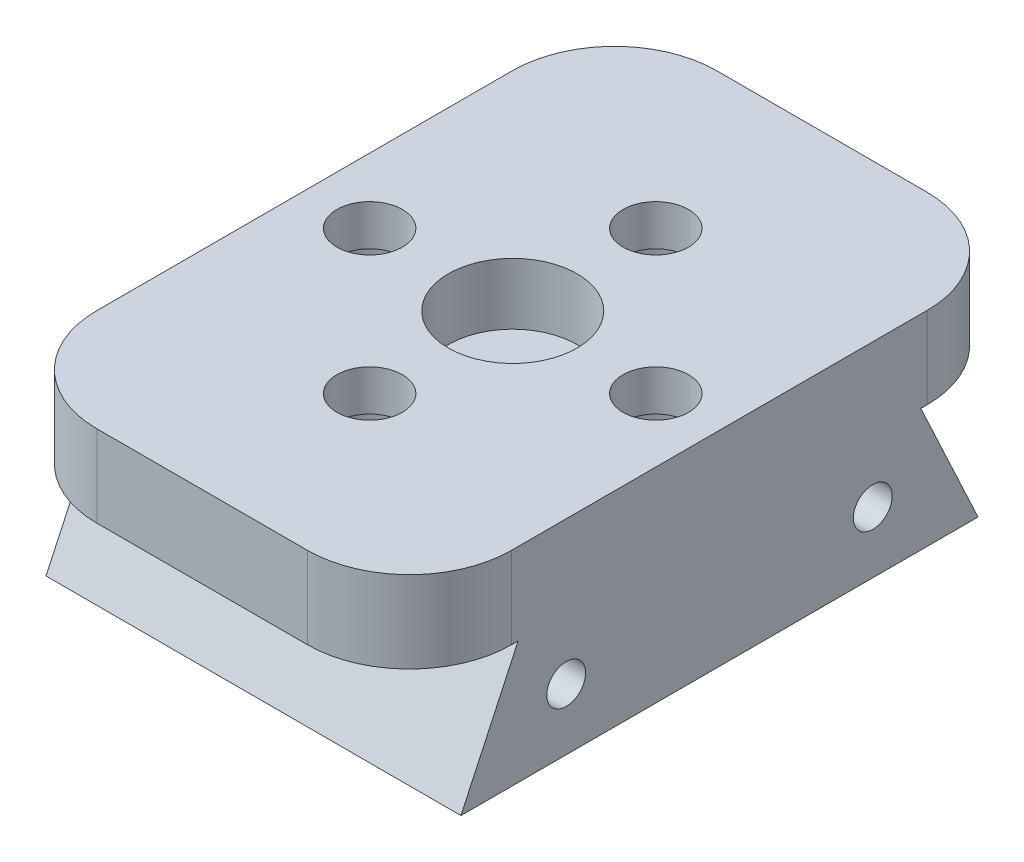
SolidWorks part; units mm, degrees
ref_plane "前视基准面" through (0, 0, 0) normal (0, 0, 1) x (1, 0, 0)
ref_plane "上视基准面" through (0, 0, 0) normal (0, 1, 0) x (1, 0, 0)
ref_plane "右视基准面" through (0, 0, 0) normal (1, 0, 0) x (0, 0, -1)
sketch "草图1" plane through (0, 0, 0) normal (0, 1, 0) x (1, 0, 0)
  line L0 (-10.185, 0) -> (10.115, 0) construction
  line L1 (-10.185, 15.165) -> (10.115, 15.165)
  line L2 (-10.185, 15.165) -> (-10.185, -15.165)
  line L3 (-10.185, -15.165) -> (10.115, -15.165)
  line L4 (10.115, 15.165) -> (10.115, -15.165)
  dimension "D1" = 20.3
  dimension "D2" = 10.115
  dimension "D3" = 30.33
extrude "凸台-拉伸1" add sketch "草图1" along normal blind 10
sketch "草图2" plane through (-10.185, 0, 0) normal (-1, 0, 0) x (0, 0, 1)
  line L0 (-15.165, 6) -> (-9.85, 6)
  line L1 (-15.165, 10) -> (-15.165, 0) construction
  line L2 (-9.85, 6) -> (-12.6478, 0)
  line L3 (-15.165, 0) -> (15.165, 0) construction
  line L5 (12.6478, 0) -> (9.85, 6)
  line L6 (9.85, 6) -> (15.165, 6)
  line L7 (15.165, 10) -> (15.165, 0) construction
  line L8 (-15.165, 6) -> (-15.165, 0)
  line L9 (-15.165, 0) -> (-12.6478, 0)
  line L10 (12.6478, 0) -> (15.165, 0)
  line L11 (15.165, 0) -> (15.165, 6)
  line L12 (0, 10) -> (0, 0) construction
  line L13 (-15.165, 10) -> (15.165, 10) construction
  dimension "D1" = 19.7
  dimension "D2" = 25.2957
  dimension "D3" = 19.7
  dimension "D4" = 65
  dimension "D5" = 6
extrude "切除-拉伸1" cut sketch "草图2" against normal through all
sketch "草图3" plane through (0, 0, 0) normal (0, -1, 0) x (1, 0, 0)
  line L0 (-7, 0) -> (7, 0) construction
  line L1 (0, -7) -> (0, 7) construction
  circle A0 centre (0, 7) radius 1.6
  circle A1 centre (7, 0) radius 1.6
  circle A2 centre (0, -7) radius 1.6
  circle A3 centre (-7, 0) radius 1.6
  point P4 (0, 0)
  point P5 (0, 0)
  dimension "D2" = 3.2
  dimension "D1" = 14
extrude "切除-拉伸2" cut sketch "草图3" against normal through all
sketch "草图4" plane through (0, 0, 0) normal (0, -1, 0) x (1, 0, 0)
  circle A0 centre (0, 7) radius 3.1
  circle A1 centre (7, 0) radius 3.1
  circle A2 centre (0, -7) radius 3.1
  circle A3 centre (-7, 0) radius 3.1
  dimension "6" = 6.2
extrude "切除-拉伸3" cut sketch "草图4" against normal offset from surface (8 mm away) 2 up to face at (7, 10, -1.6)
sketch "草图5" plane through (10.115, 0, 0) normal (1, 0, 0) x (0, 0, -1)
  line L0 (-11.2489, 3) -> (11.2489, 3) construction
  line L1 (-9.85, 6) -> (-12.6478, 0) construction
  line L2 (12.6478, 0) -> (9.85, 6) construction
  line L3 (-12.6478, 0) -> (12.6478, 0) construction
  line L4 (0, 0) -> (0, 3) construction
  circle A0 centre (-7.5, 3) radius 0.95
  circle A1 centre (7.5, 3) radius 0.95
  dimension "D2" = 15
  dimension "D3" = 1.9
  dimension "D1" = 3
extrude "切除-拉伸4" cut sketch "草图5" against normal blind 5
sketch "草图6" plane through (0, 10, 0) normal (0, 1, 0) x (1, 0, 0)
  circle A0 centre (0, 0) radius 3.15
  dimension "D1" = 6.3
extrude "切除-拉伸5" cut sketch "草图6" against normal blind 3
fillet "圆角2" radius 5 4 edges at (-10.185, 8, 15.165) (10.115, 8, 15.165) (-10.185, 8, -15.165) (10.115, 8, -15.165)
